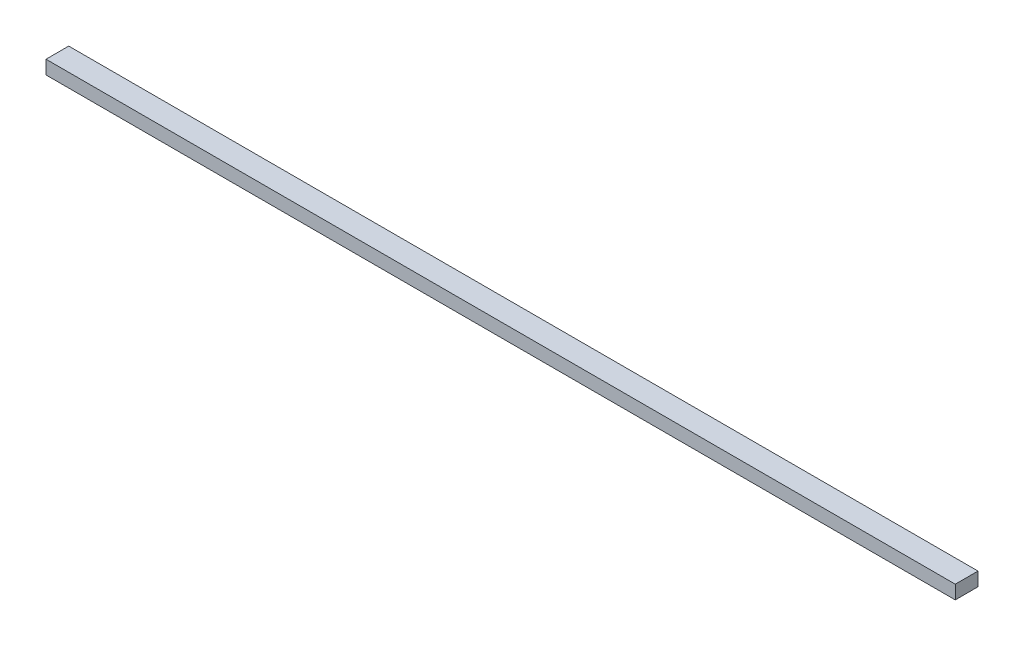
SolidWorks part; units mm, degrees
ref_plane "Front Plane" through (0, 0, 0) normal (0, 0, 1) x (1, 0, 0)
ref_plane "Top Plane" through (0, 0, 0) normal (0, 1, 0) x (1, 0, 0)
ref_plane "Right Plane" through (0, 0, 0) normal (1, 0, 0) x (0, 0, -1)
sketch "Sketch1" plane through (0, 0, 0) normal (0, 1, 0) x (1, 0, 0)
  line L1 (0, 0) -> (200, 0)
  line L2 (0, 0) -> (0, 5)
  line L3 (0, 5) -> (200, 5)
  line L4 (200, 0) -> (200, 5)
  dimension "D1" = 200
  dimension "D2" = 5
extrude "Boss-Extrude1" add sketch "Sketch1" along normal blind 3
